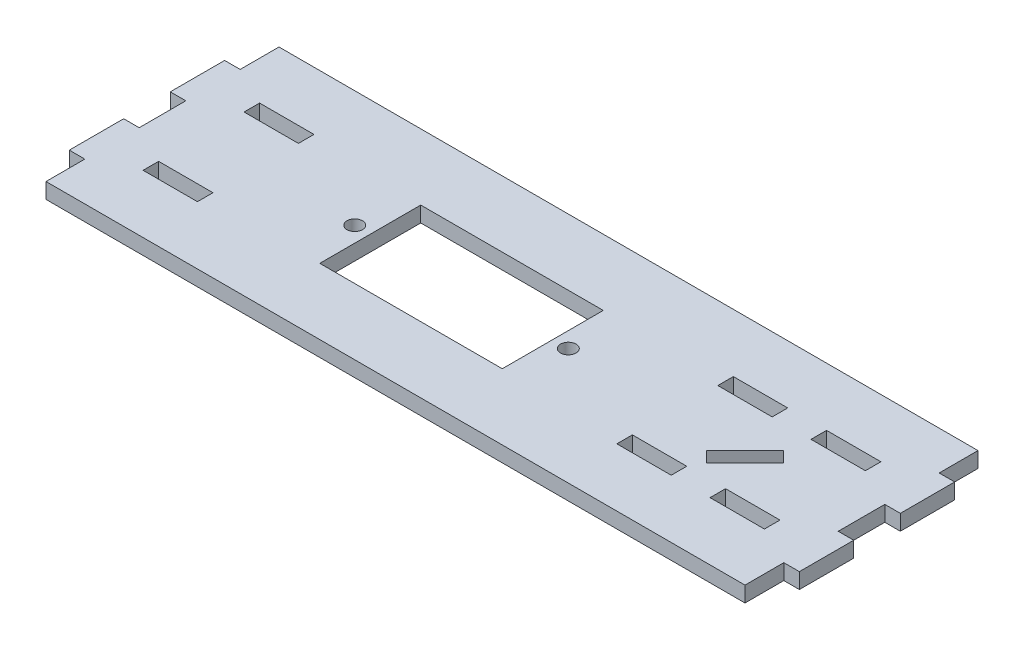
SolidWorks part; units mm, degrees
ref_plane "Front Plane" through (0, 0, 0) normal (0, 0, 1) x (1, 0, 0)
ref_plane "Top Plane" through (0, 0, 0) normal (0, 1, 0) x (1, 0, 0)
ref_plane "Right Plane" through (0, 0, 0) normal (1, 0, 0) x (0, 0, -1)
sketch "Sketch1" plane through (0, 0, 0) normal (0, 1, 0) x (1, 0, 0)
  line L1 (-23.0501, 13.8238) -> (66.9499, 13.8238)
  line L2 (-23.0501, 13.8238) -> (-23.0501, -16.1762)
  line L3 (-23.0501, -16.1762) -> (66.9499, -16.1762)
  line L4 (66.9499, 13.8238) -> (66.9499, -16.1762)
  line L5 (3.6999, 5.3238) -> (27.1999, 5.3238)
  line L6 (3.6999, 5.3238) -> (3.6999, -7.6762)
  line L7 (3.6999, -7.6762) -> (27.1999, -7.6762)
  line L8 (27.1999, 5.3238) -> (27.1999, -7.6762)
  line L9 (-23.0501, -11.1762) -> (-25.0501, -11.1762)
  line L10 (-23.0501, -11.1762) -> (-23.0501, -4.1762)
  line L11 (-23.0501, -4.1762) -> (-25.0501, -4.1762)
  line L12 (-25.0501, -11.1762) -> (-25.0501, -4.1762)
  line L13 (-23.0501, 1.8238) -> (-25.0501, 1.8238)
  line L14 (-23.0501, 1.8238) -> (-23.0501, 8.8238)
  line L15 (-23.0501, 8.8238) -> (-25.0501, 8.8238)
  line L16 (-25.0501, 1.8238) -> (-25.0501, 8.8238)
  line L17 (66.9499, -11.1762) -> (68.9499, -11.1762)
  line L18 (66.9499, -11.1762) -> (66.9499, -4.1762)
  line L19 (66.9499, -4.1762) -> (68.9499, -4.1762)
  line L20 (68.9499, -11.1762) -> (68.9499, -4.1762)
  line L21 (66.9499, 1.8238) -> (68.9499, 1.8238)
  line L22 (66.9499, 1.8238) -> (66.9499, 8.8238)
  line L23 (66.9499, 8.8238) -> (68.9499, 8.8238)
  line L24 (68.9499, 1.8238) -> (68.9499, 8.8238)
  line L25 (61.9499, 6.3238) -> (54.9499, 6.3238)
  line L26 (61.9499, 6.3238) -> (61.9499, 4.3238)
  line L27 (61.9499, 4.3238) -> (54.9499, 4.3238)
  line L28 (54.9499, 6.3238) -> (54.9499, 4.3238)
  line L29 (54.9499, -6.6762) -> (61.9499, -6.6762)
  line L30 (54.9499, -6.6762) -> (54.9499, -8.6762)
  line L31 (54.9499, -8.6762) -> (61.9499, -8.6762)
  line L32 (61.9499, -6.6762) -> (61.9499, -8.6762)
  line L33 (42.9499, 6.3238) -> (49.9499, 6.3238)
  line L34 (42.9499, 6.3238) -> (42.9499, 4.3238)
  line L35 (42.9499, 4.3238) -> (49.9499, 4.3238)
  line L36 (49.9499, 6.3238) -> (49.9499, 4.3238)
  line L37 (42.9499, -6.6762) -> (49.9499, -6.6762)
  line L38 (42.9499, -6.6762) -> (42.9499, -8.6762)
  line L39 (42.9499, -8.6762) -> (49.9499, -8.6762)
  line L40 (49.9499, -6.6762) -> (49.9499, -8.6762)
  line L41 (-18.0501, 6.3238) -> (-11.0501, 6.3238)
  line L42 (-18.0501, 6.3238) -> (-18.0501, 4.3238)
  line L43 (-18.0501, 4.3238) -> (-11.0501, 4.3238)
  line L44 (-11.0501, 6.3238) -> (-11.0501, 4.3238)
  line L45 (-18.0501, -6.6762) -> (-11.0501, -6.6762)
  line L46 (-18.0501, -6.6762) -> (-18.0501, -8.6762)
  line L47 (-18.0501, -8.6762) -> (-11.0501, -8.6762)
  line L48 (-11.0501, -6.6762) -> (-11.0501, -8.6762)
  line L49 (50.8902, -5.0641) -> (55.8399, -0.1143)
  line L50 (50.8902, -5.0641) -> (49.4759, -3.6498)
  line L51 (55.8399, -0.1143) -> (54.4257, 1.2999)
  line L52 (49.4759, -3.6498) -> (54.4257, 1.2999)
  circle A0 centre (1.6999, -1.1762) radius 1
  circle A1 centre (29.1999, -1.1762) radius 1
  point P28 (27.1999, -1.1762)
  point P53 (0, 0)
  dimension "D24" = 2
  dimension "D25" = 2
  dimension "D1" = 13
  dimension "D2" = 23.5
  dimension "D3" = 39.75
  dimension "D4" = 90
  dimension "D5" = 30
  dimension "D6" = 8.5
  dimension "D7" = 8.5
  dimension "D8" = 2
  dimension "D9" = 7
  dimension "D10" = 7
  dimension "D11" = 2
  dimension "D12" = 5
  dimension "D13" = 5
  dimension "D14" = 2
  dimension "D15" = 2
  dimension "D16" = 7
  dimension "D17" = 7
  dimension "D18" = 5
  dimension "D19" = 5
  dimension "D20" = 6
  dimension "D21" = 6
  dimension "D22" = 2
  dimension "D23" = 2
  dimension "D26" = 7
  dimension "D27" = 7
  dimension "D28" = 2
  dimension "D29" = 2
  dimension "D30" = 7
  dimension "D31" = 7
  dimension "D32" = 7
  dimension "D33" = 7
  dimension "D34" = 2
  dimension "D35" = 2
  dimension "D36" = 2
  dimension "D37" = 2
  dimension "D38" = 5
  dimension "D39" = 5
  dimension "D40" = 5
  dimension "D41" = 5
  dimension "D42" = 5
  dimension "D43" = 5
  dimension "D44" = 7.5
  dimension "D45" = 11
  dimension "D46" = 7.5
  dimension "D47" = 2.5
  dimension "D48" = 2.5
  dimension "D49" = 2.5
  dimension "D50" = 2.5
  dimension "D51" = 7.5
  dimension "D52" = 11
  dimension "D53" = 7.5
  dimension "D54" = 7.5
  dimension "D55" = 11
  dimension "D56" = 7.5
  dimension "D57" = 6.5
  dimension "D58" = 6.5
  dimension "D59" = 6.5
  dimension "D60" = 45
  dimension "D61" = 2
  dimension "D62" = 7
  dimension "D63" = 12.5239
  dimension "D64" = 11.11
extrude "Boss-Extrude1" add sketch "Sketch1" along normal blind 2
